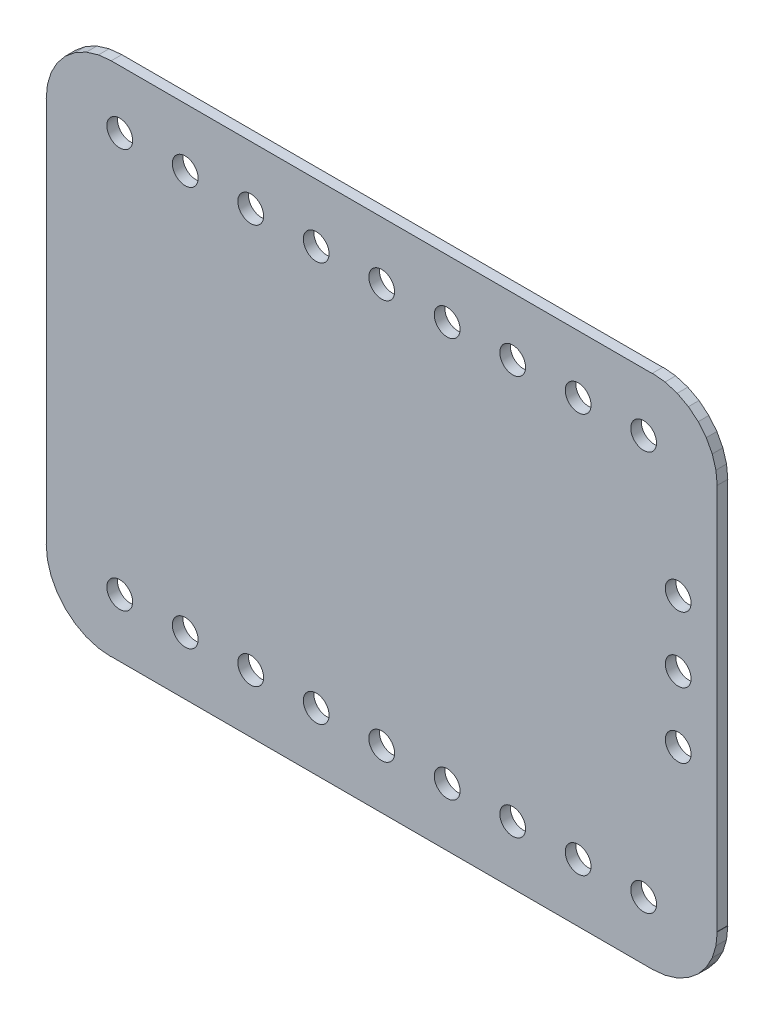
SolidWorks part; units mm, degrees
ref_plane "前视基准面" through (0, 0, 0) normal (0, 0, 1) x (1, 0, 0)
ref_plane "上视基准面" through (0, 0, 0) normal (0, 1, 0) x (1, 0, 0)
ref_plane "右视基准面" through (0, 0, 0) normal (1, 0, 0) x (0, 0, -1)
sketch "草图1" plane through (0, 0, 0) normal (0, 0, 1) x (1, 0, 0)
  line L0 (-23.9901, 0.0362) -> (-23.5, -0.0121)
  line L1 (-23.5, -0.0121) -> (-23.5, 0)
  line L2 (-23.5, 0) -> (-2.5, -0.0121)
  line L3 (-2.5, -0.0121) -> (-2.0099, 0.0362)
  line L4 (-2.0099, 0.0362) -> (-1.5387, 0.1791)
  line L5 (-1.5387, 0.1791) -> (-1.1044, 0.4113)
  line L6 (-1.1044, 0.4113) -> (-0.7237, 0.7237)
  line L7 (-0.7237, 0.7237) -> (-0.4113, 1.1044)
  line L8 (-0.4113, 1.1044) -> (-0.1791, 1.5387)
  line L9 (-0.1791, 1.5387) -> (-0.0362, 2.0099)
  line L10 (-0.0362, 2.0099) -> (0.0121, 2.5)
  line L11 (0.0121, 2.5) -> (0, 2.5)
  line L12 (0, 2.5) -> (0, 17.5)
  line L13 (0, 17.5) -> (0.0121, 17.5)
  line L14 (0.0121, 17.5) -> (-0.0362, 17.9901)
  line L15 (-0.0362, 17.9901) -> (-0.1791, 18.4613)
  line L16 (-0.1791, 18.4613) -> (-0.4113, 18.8956)
  line L17 (-0.4113, 18.8956) -> (-0.7237, 19.2763)
  line L18 (-0.7237, 19.2763) -> (-1.1044, 19.5887)
  line L19 (-1.1044, 19.5887) -> (-1.5387, 19.8209)
  line L20 (-1.5387, 19.8209) -> (-2.0099, 19.9638)
  line L21 (-2.0099, 19.9638) -> (-2.5, 20.0121)
  line L22 (-2.5, 20.0121) -> (-2.5, 20)
  line L23 (-2.5, 20) -> (-23.492, 20.0121)
  line L24 (-23.492, 20.0121) -> (-23.9837, 19.9637)
  line L25 (-23.9837, 19.9637) -> (-24.4564, 19.8203)
  line L26 (-24.4564, 19.8203) -> (-24.8921, 19.5874)
  line L27 (-24.8921, 19.5874) -> (-25.274, 19.274)
  line L28 (-25.274, 19.274) -> (-25.5874, 18.8921)
  line L29 (-25.5874, 18.8921) -> (-25.8203, 18.4564)
  line L30 (-25.8203, 18.4564) -> (-25.9637, 17.9837)
  line L31 (-25.9637, 17.9837) -> (-26.0122, 17.492)
  line L32 (-26.0122, 17.492) -> (-26, 17.492)
  line L33 (-26, 17.492) -> (-26, 2.5)
  line L34 (-26, 2.5) -> (-26.0121, 2.5)
  line L35 (-26.0121, 2.5) -> (-25.9638, 2.0099)
  line L36 (-25.9638, 2.0099) -> (-25.8209, 1.5387)
  line L37 (-25.8209, 1.5387) -> (-25.5887, 1.1044)
  line L38 (-25.5887, 1.1044) -> (-25.2763, 0.7237)
  line L39 (-25.2763, 0.7237) -> (-24.8956, 0.4113)
  line L40 (-24.8956, 0.4113) -> (-24.4613, 0.1791)
  line L41 (-24.4613, 0.1791) -> (-23.9901, 0.0362)
  circle A0 centre (-23.16, 17.75) radius 0.5
  circle A1 centre (-20.62, 17.75) radius 0.5
  circle A2 centre (-20.62, 2.25) radius 0.5
  circle A3 centre (-15.54, 17.75) radius 0.5
  circle A4 centre (-13, 17.75) radius 0.5
  circle A5 centre (-18.08, 17.75) radius 0.5
  circle A6 centre (-18.08, 2.25) radius 0.5
  circle A7 centre (-15.54, 2.25) radius 0.5
  circle A8 centre (-23.16, 2.25) radius 0.5
  circle A9 centre (-10.46, 2.25) radius 0.5
  circle A10 centre (-13, 2.25) radius 0.5
  circle A11 centre (-7.92, 17.75) radius 0.5
  circle A12 centre (-5.38, 17.75) radius 0.5
  circle A13 centre (-10.46, 17.75) radius 0.5
  circle A14 centre (-2.84, 17.75) radius 0.5
  circle A15 centre (-1.5, 13.04) radius 0.5
  circle A16 centre (-5.38, 2.25) radius 0.5
  circle A17 centre (-2.84, 2.25) radius 0.5
  circle A18 centre (-7.92, 2.25) radius 0.5
  circle A19 centre (-1.5, 10.5) radius 0.5
  circle A20 centre (-1.5, 7.96) radius 0.5
extrude "凸台-拉伸1" add sketch "草图1" against normal blind 0.4115
sketch "草图2" plane through (0, 0, -0.4115) normal (0, 0, -1) x (-1, 0, 0)
  line L0 (97.8217, 228.0446) -> (489.8217, 228.0446) construction
sketch "草图3" plane through (0, 0, 0) normal (0, 0, 1) x (1, 0, 0)
  line L0 (72.0234, 226.6183) -> (464.6901, 226.6183) construction
